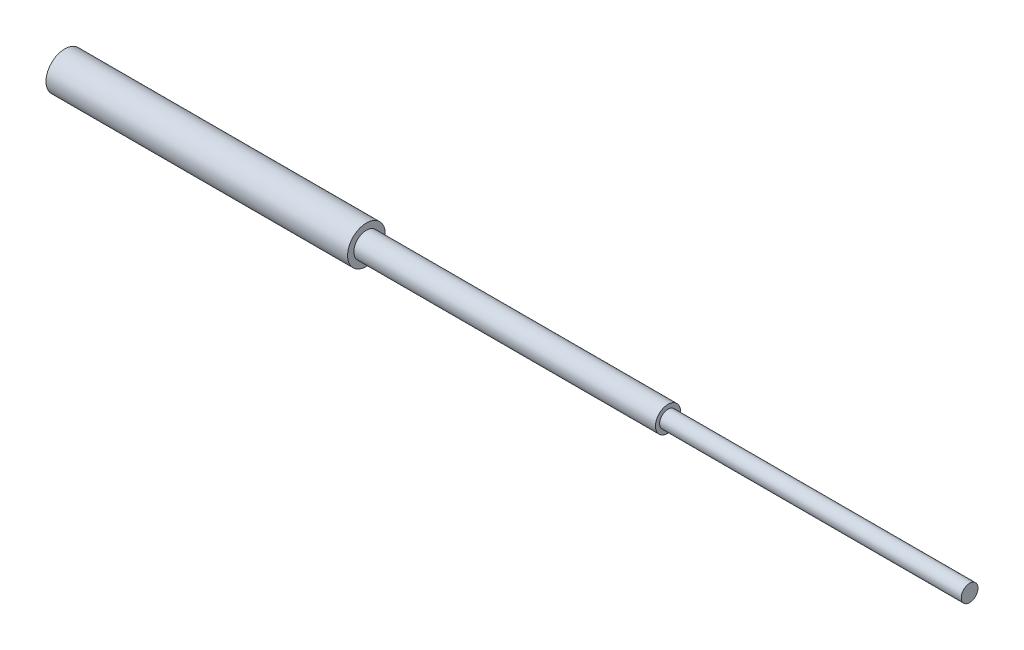
SolidWorks part; units mm, degrees
material "1345 Alloy"
ref_plane "Front Plane" through (0, 0, 0) normal (0, 0, 1) x (1, 0, 0)
ref_plane "Top Plane" through (0, 0, 0) normal (0, 1, 0) x (1, 0, 0)
ref_plane "Right Plane" through (0, 0, 0) normal (1, 0, 0) x (0, 0, -1)
other "Configuration Table"
sketch "Sketch1" plane through (0, 0, 0) normal (1, 0, 0) x (0, 0, -1)
  circle A0 centre (0, 0) radius 28.575
  dimension "D1" = 57.15
extrude "Extrude1" add sketch "Sketch1" along normal blind 457.2
sketch "Sketch2" plane through (457.2, 0, 0) normal (1, 0, 0) x (0, 0, -1)
  circle A0 centre (0, 0) radius 19.05
  dimension "D1" = 38.1
extrude "Extrude2" add sketch "Sketch2" along normal blind 457.2
sketch "Sketch4" plane through (914.4, 0, 0) normal (1, 0, 0) x (0, 0, -1)
  circle A0 centre (0, 0) radius 12.7
  dimension "D1" = 25.4
extrude "Extrude3" add sketch "Sketch4" along normal blind 457.2
fillet "Fillet6" [suppressed] radius 3.175
